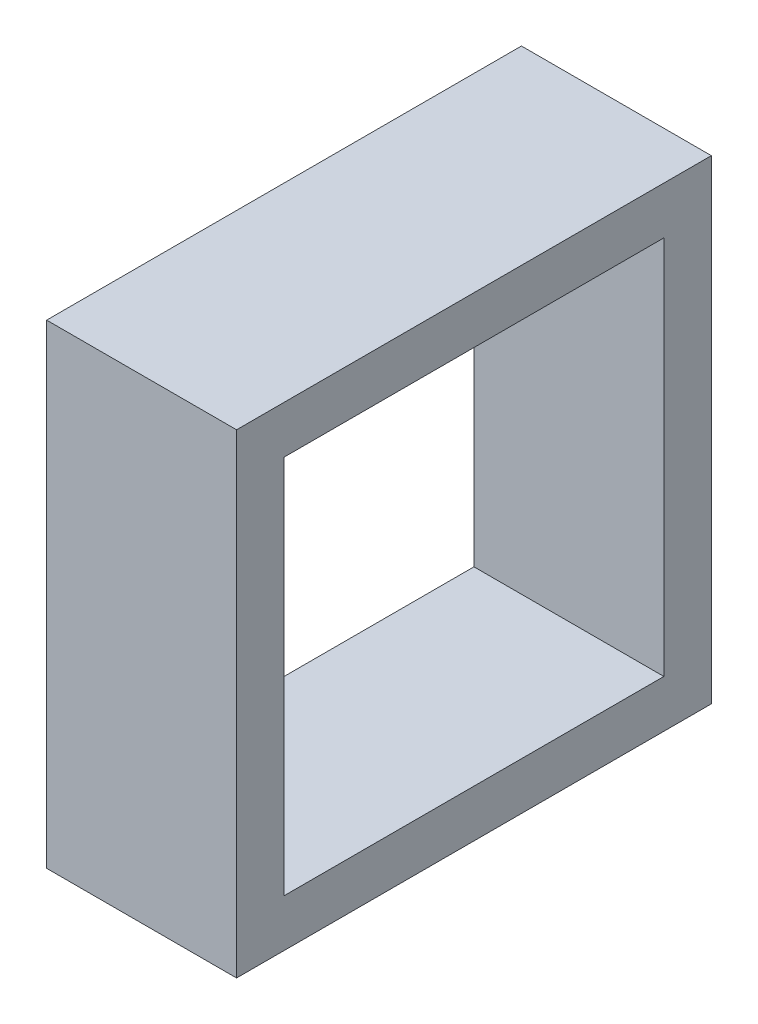
SolidWorks part; units mm, degrees
ref_plane "前视基准面" through (0, 0, 0) normal (0, 0, 1) x (1, 0, 0)
ref_plane "上视基准面" through (0, 0, 0) normal (0, 1, 0) x (1, 0, 0)
ref_plane "右视基准面" through (0, 0, 0) normal (1, 0, 0) x (0, 0, -1)
other "Configuration Table"
sketch "草图1" plane through (0, 0, 0) normal (1, 0, 0) x (0, 0, -1)
  line L1 (-10, -10) -> (10, -10)
  line L2 (-10, -10) -> (-10, 10)
  line L3 (-10, 10) -> (10, 10)
  line L4 (10, -10) -> (10, 10)
  line L5 (-10, -10) -> (10, 10) construction
  line L6 (-10, 10) -> (10, -10) construction
  line L7 (-12.5, -12.5) -> (12.5, -12.5)
  line L8 (-12.5, -12.5) -> (-12.5, 12.5)
  line L9 (-12.5, 12.5) -> (12.5, 12.5)
  line L10 (12.5, -12.5) -> (12.5, 12.5)
  line L11 (-12.5, -12.5) -> (12.5, 12.5) construction
  line L12 (-12.5, 12.5) -> (12.5, -12.5) construction
  point P0 (0, 0)
  point P6 (0, 0)
  dimension "D1" = 20
  dimension "D2" = 20
  dimension "D3" = 25
  dimension "D4" = 25
extrude "凸台-拉伸1" add sketch "草图1" along normal blind 10
